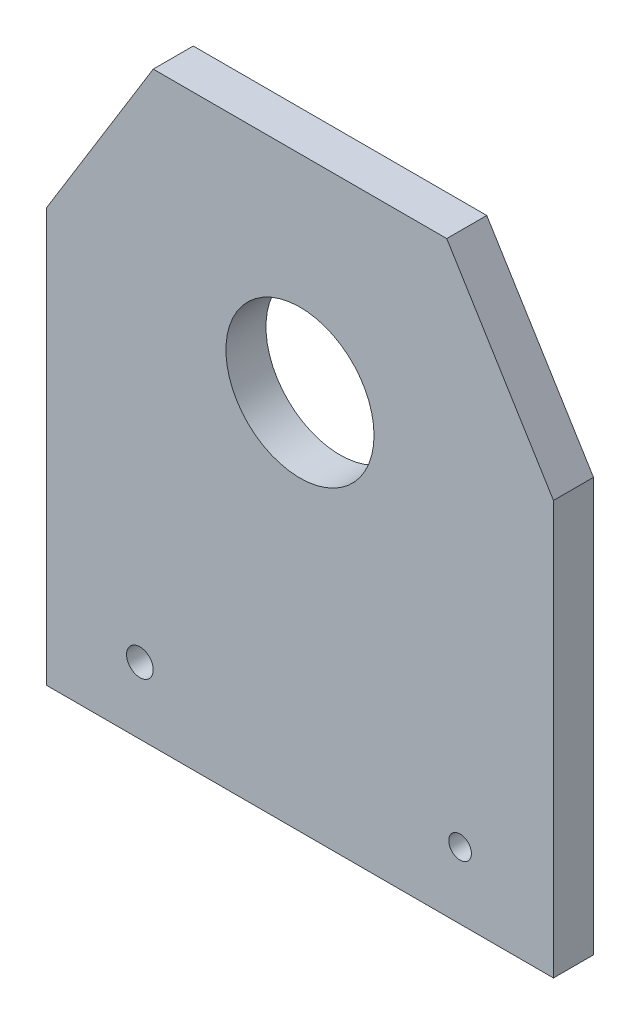
SolidWorks part; units mm, degrees
ref_plane "Спереди" through (0, 0, 0) normal (0, 0, 1) x (1, 0, 0)
ref_plane "Сверху" through (0, 0, 0) normal (0, 1, 0) x (1, 0, 0)
ref_plane "Справа" through (0, 0, 0) normal (1, 0, 0) x (0, 0, -1)
other "Configuration Table"
sketch "Эскиз1" plane through (0, 0, 0) normal (0, 0, 1) x (1, 0, 0)
  line L0 (-38, 0) -> (38, 0)
  line L1 (38, 0) -> (38, 62)
  line L2 (38, 62) -> (22, 88)
  line L3 (22, 88) -> (-22, 88)
  line L4 (-22, 88) -> (-38, 62)
  line L5 (-38, 62) -> (-38, 0)
  circle A0 centre (0, 57) radius 11.1
  circle A1 centre (-24, 10) radius 2
  circle A2 centre (24, 10) radius 1.7
extrude "08_Tilt_idler_cheek" add sketch "Эскиз1" along normal blind 6
